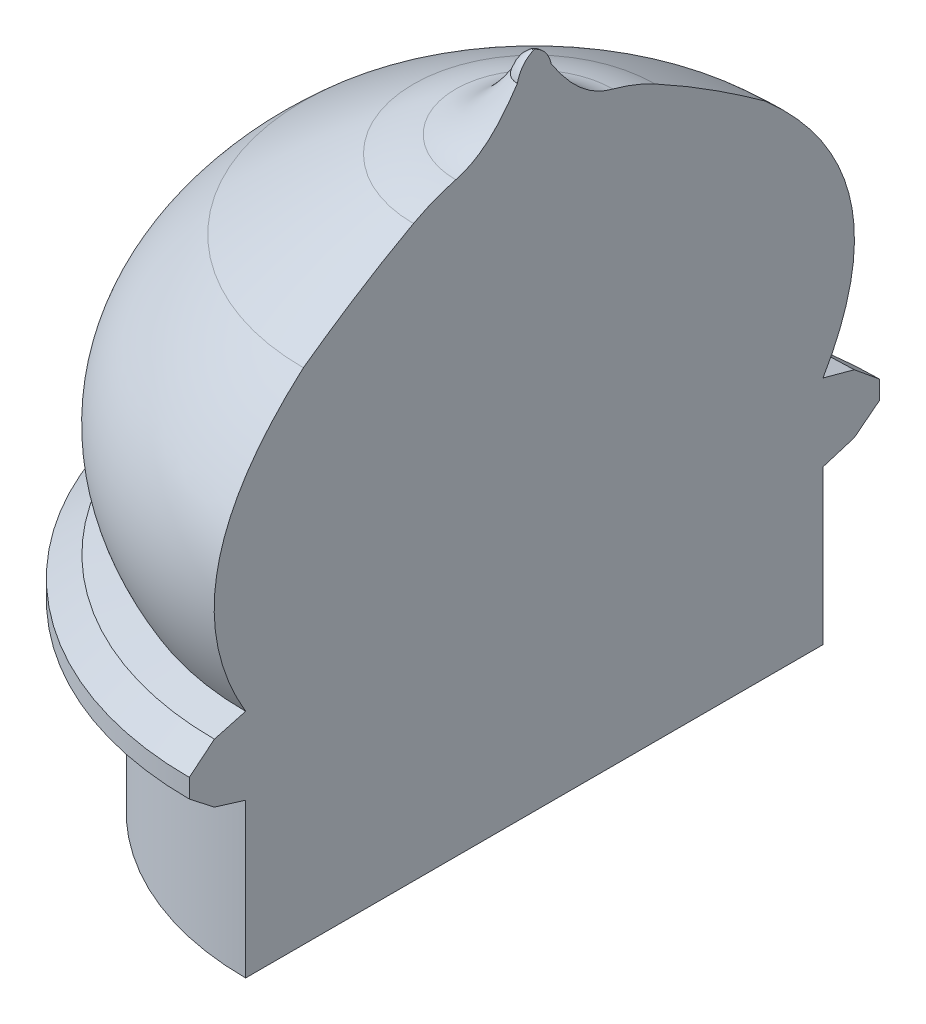
SolidWorks part; units mm, degrees
material "ABS"
ref_plane "Front Plane" through (0, 0, 0) normal (0, 0, 1) x (1, 0, 0)
ref_plane "Top Plane" through (0, 0, 0) normal (0, 1, 0) x (1, 0, 0)
ref_plane "Right Plane" through (0, 0, 0) normal (1, 0, 0) x (0, 0, -1)
sketch "Sketch4" plane through (0, 0, 0) normal (1, 0, 0) x (0, 0, -1)
  line L0 (0, 43.5542) -> (0, 0)
  line L1 (0, 0) -> (-19.05, 0)
  line L2 (-19.05, 0) -> (-19.05, 10.16)
  line L3 (-22.7678, 18.4174) -> (-22.7678, 3.0059) construction
  line L4 (-19.05, 10.16) -> (-21.1117, 10.795)
  line L5 (-21.1117, 10.795) -> (-22.7678, 12.0846)
  line L6 (-22.7678, 12.0846) -> (-22.7678, 13.3233)
  line L7 (-22.7678, 13.3233) -> (-21.1117, 14.6806)
  line L8 (-19.05, 0) -> (-24.13, 0) construction
  line L9 (-21.1117, 14.6806) -> (-19.05, 15.24)
  line L10 (-19.05, 0) -> (-21.1117, 0) construction
  line L11 (-21.1117, 0) -> (-21.1117, 21.59) construction
  line L12 (-19.05, 0) -> (-19.05, 25.4) construction
  line L13 (-19.05, 0) -> (-15.24, 0) construction
  line L14 (-15.24, 0) -> (-15.24, 29.21) construction
  arc A0 (-5.1864, 38.6864) -> (-7.9738, 37.5788) centre (-1.9232, 26.4128) ccw
  spline S0 degree 2 poles (-19.05, 15.24) (-24.6196, 24.7131) (-15.24, 32.9696) knots 0 0 0 1 1 1
  spline S1 degree 3 poles (-15.24, 32.9696) (-13.1591, 34.4668) (-10.7541, 36.0447) (-8.2424, 37.4333) (-7.9738, 37.5788) knots 0 0 0 0 0.730138 0.817134 0.817134 0.817134 0.817134
  spline S2 degree 3 poles (-5.1864, 38.6864) (-3.3511, 39.151) (-2.1048, 40.6568) (-1.1186, 42.1563) knots 0 0 0 0 1 1 1 1
  spline S3 degree 2 poles (-1.1186, 42.1563) (-0.8861, 43.1585) (0, 43.5542) knots 0 0 0 1 1 1
  point P6 (-21.6197, 10.16)
  point P7 (-21.6197, 15.24)
  point P8 (-22.7678, 15.24)
  point P10 (-22.7678, 10.1901)
  dimension "D1" = 12.7
revolve "Revolve1" add sketch "Sketch4" angle 180 about L0
sketch3d "3DSketch2" plane through (0, 0, 0) normal (0, 0, 1) x (1, 0, 0)
sketch3d "3DSketch3" plane through (0, 0, 0) normal (0, 0, 1) x (1, 0, 0)
sketch3d "3DSketch5" plane through (0, 0, 0) normal (0, 0, 1) x (1, 0, 0)
